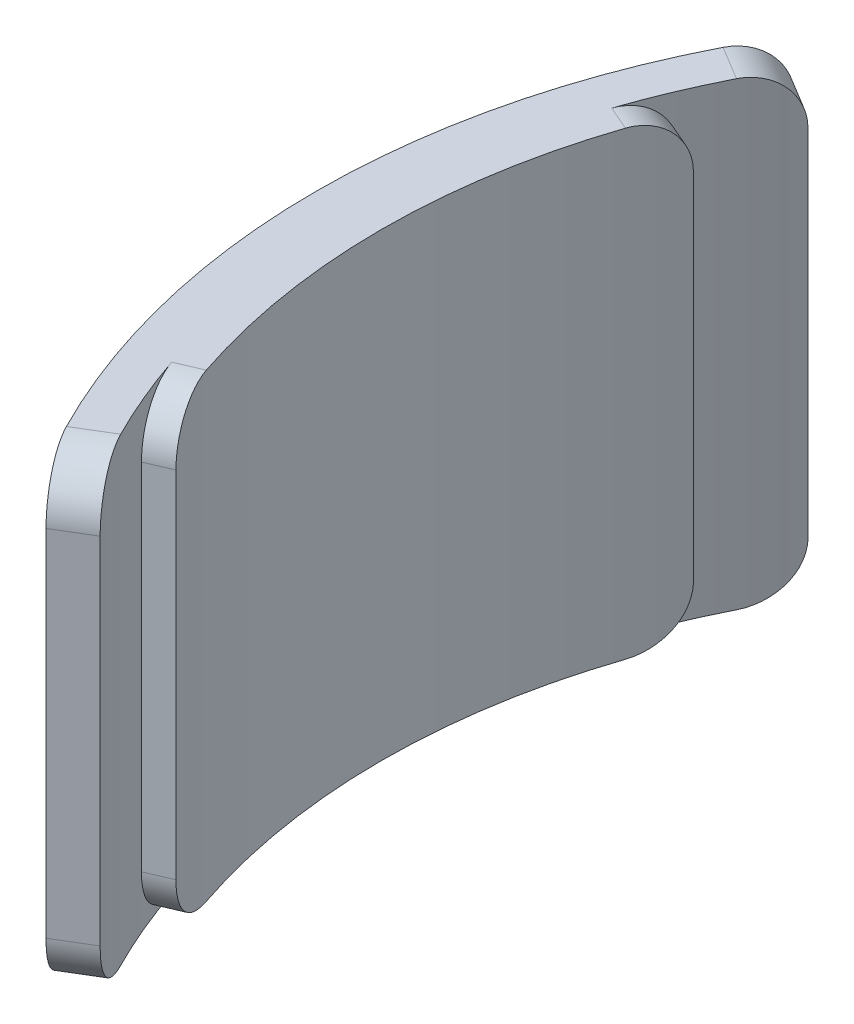
SolidWorks part; units mm, degrees
ref_plane "Front Plane" through (0, 0, 0) normal (0, 0, 1) x (1, 0, 0)
ref_plane "Top Plane" through (0, 0, 0) normal (0, 1, 0) x (1, 0, 0)
ref_plane "Right Plane" through (0, 0, 0) normal (1, 0, 0) x (0, 0, -1)
sketch "Sketch1" plane through (0, 0, 0) normal (0, 1, 0) x (1, 0, 0)
  line L3 (0, 0) -> (-47.8004, 20.4725)
  line L4 (-47.8004, 20.4725) -> (-47.8004, -20.4725) construction
  line L5 (-47.8004, -20.4725) -> (0, 0)
  line L6 (0, 0) -> (-47.0525, -28.4792)
  line L7 (-47.0525, 28.4792) -> (0, 0)
  line L8 (0, 52) -> (0, 50)
  line L9 (0, 50) -> (0, 48)
  circle A0 centre (0, 0) radius 52
  circle A1 centre (0, 0) radius 48
  circle A2 centre (0, 0) radius 55
  circle A3 centre (0, 0) radius 50
  point P10 (-47.0525, -28.4792)
other "Pen Sketch1" parameters "D2"=95.4749, "D3"=79.2031, "D4"=102, "D6"=101, "D1"=68.192, "D5"=6.8663
extrude "Boss-Extrude1" add sketch "Sketch1" along normal blind 35 contours L7 A2 L6 A0 | L4 A0 A3 | A3 L4 L5 | L3 L4 A3
fillet "Fillet1" radius 4 4 edges at (-46.8812, 0, -20.0788) (-46.8812, 0, 20.0788) (-46.8812, 35, -20.0788) (-46.8812, 35, 20.0788)
fillet "Fillet2" radius 4 4 edges at (-45.7692, 35, -27.7025) (-45.7692, 0, -27.7025) (-45.7692, 35, 27.7025) (-45.7692, 0, 27.7025)
